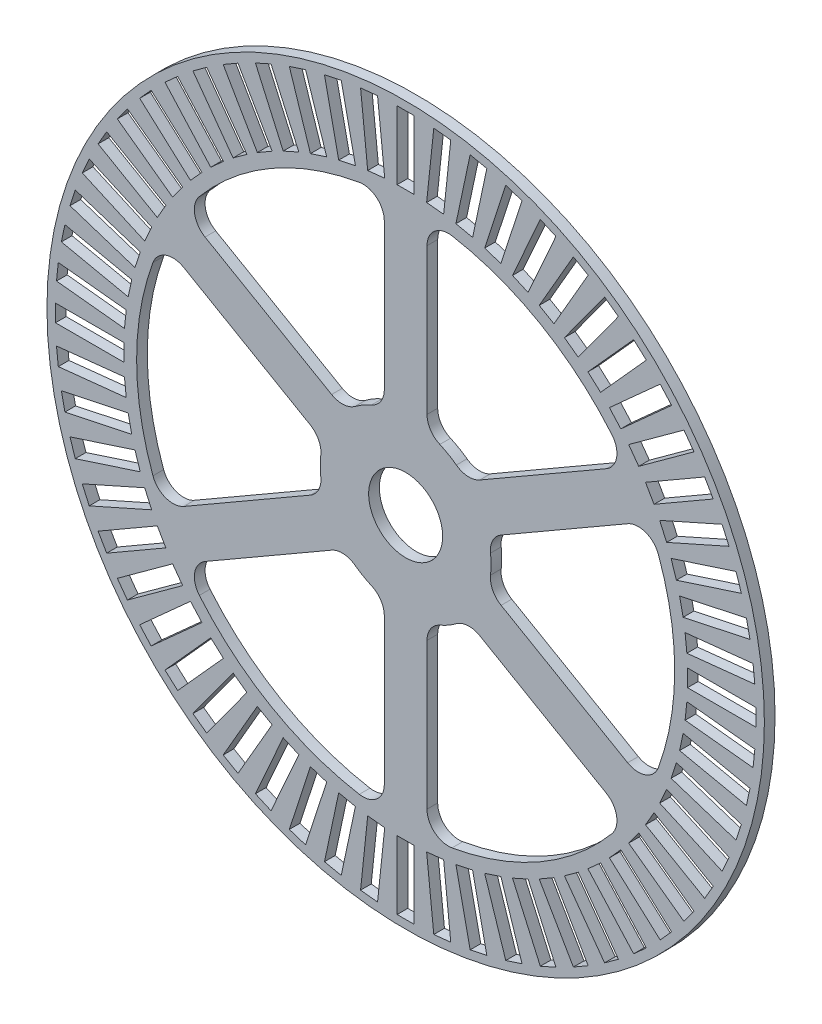
SolidWorks part; units mm, degrees
material "1023 Carbon Steel Sheet (SS)"
ref_plane "Front Plane" through (0, 0, 0) normal (0, 0, 1) x (1, 0, 0)
ref_plane "Top Plane" through (0, 0, 0) normal (0, 1, 0) x (1, 0, 0)
ref_plane "Right Plane" through (0, 0, 0) normal (1, 0, 0) x (0, 0, -1)
sketch "Sketch1" plane through (0, 0, 0) normal (0, 0, 1) x (1, 0, 0)
  circle A0 centre (0, 0) radius 40.005
  circle A1 centre (0, 0) radius 53.34
  dimension "D1" = 106.68
  dimension "D2" = 13.335
extrude "Boss-Extrude1" add sketch "Sketch1" along normal blind 1.5875
sketch "Sketch4" plane through (0, 0, 1.5875) normal (0, 0, 1) x (1, 0, 0)
  line L1 (-1.27, 52.07) -> (1.27, 52.07)
  line L2 (-1.27, 52.07) -> (-1.27, 41.91)
  line L3 (-1.27, 41.91) -> (1.27, 41.91)
  line L4 (1.27, 52.07) -> (1.27, 41.91)
  line L5 (-1.27, 52.07) -> (1.27, 41.91) construction
  line L6 (-1.27, 41.91) -> (1.27, 52.07) construction
  point P0 (0, 46.99)
  dimension "D1" = 2.54
  dimension "D2" = 10.16
  dimension "D3" = 46.99
extrude "Cut-Extrude3" cut sketch "Sketch4" against normal blind 5.08 contours L1 L4 L3 L2
pattern_circular "CirPattern2" count 60 over 360 about axis through (0, 0, 0) along (0, 0, 1) of "Cut-Extrude3"
sketch "Sketch7" plane through (0, 0, 0) normal (0, 0, -1) x (-1, 0, 0)
  line L0 (-1.905, 0) -> (49998.095, 0) construction
  circle A2 centre (60.325, 0) radius 6.985
  point P6 (60.325, 0)
  dimension "D1" = 60.325
  dimension "D2" = 13.97
extrude "Cut-Extrude5" [suppressed] cut sketch "Sketch7" against normal blind 2.54
pattern_circular "CirPattern4" [suppressed] count 6 over 360
sketch "Sketch8" plane through (0, 0, 0) normal (0, 0, 1) x (1, 0, 0)
  line L0 (-3.175, 12.2967) -> (-3.175, 39.8788)
  line L1 (3.175, 12.2967) -> (3.175, 39.8788)
  line L2 (9.0618, 8.898) -> (32.9486, 22.689)
  line L3 (12.2368, 3.3987) -> (36.1236, 17.1898)
  line L4 (12.2368, -3.3987) -> (36.1236, -17.1898)
  line L5 (9.0618, -8.898) -> (32.9486, -22.689)
  line L6 (3.175, -12.2967) -> (3.175, -39.8788)
  line L7 (-3.175, -12.2967) -> (-3.175, -39.8788)
  line L8 (-9.0618, -8.898) -> (-32.9486, -22.689)
  line L9 (-12.2368, -3.3987) -> (-36.1236, -17.1898)
  line L10 (-12.2368, 3.3987) -> (-36.1236, 17.1898)
  line L11 (-9.0618, 8.898) -> (-32.9486, 22.689)
  circle A1 centre (0, 0) radius 40.005 construction
  arc A2 (-32.9486, 22.689) -> (-36.1236, 17.1898) centre (0, 0) ccw
  arc A3 (-36.1236, -17.1898) -> (-32.9486, -22.689) centre (0, 0) ccw
  arc A4 (-3.175, -39.8788) -> (3.175, -39.8788) centre (0, 0) ccw
  arc A5 (32.9486, -22.689) -> (36.1236, -17.1898) centre (0, 0) ccw
  arc A6 (36.1236, 17.1898) -> (32.9486, 22.689) centre (0, 0) ccw
  arc A7 (3.175, 39.8788) -> (-3.175, 39.8788) centre (0, 0) ccw
  circle A8 centre (0, 0) radius 5.5
  arc A9 (-12.2368, 3.3987) -> (-12.2368, -3.3987) centre (0, 0) ccw
  arc A10 (-3.175, 12.2967) -> (-9.0618, 8.898) centre (0, 0) ccw
  arc A11 (9.0618, 8.898) -> (3.175, 12.2967) centre (0, 0) ccw
  arc A12 (12.2368, -3.3987) -> (12.2368, 3.3987) centre (0, 0) ccw
  arc A13 (3.175, -12.2967) -> (9.0618, -8.898) centre (0, 0) ccw
  arc A14 (-9.0618, -8.898) -> (-3.175, -12.2967) centre (0, 0) ccw
  point P32 (0, 0)
  dimension "D1" = 11
  dimension "D4" = 25.4
  dimension "D2" = 6.35
  dimension "D3" = 6
extrude "Boss-Extrude2" add sketch "Sketch8" along normal blind 1.5875
fillet "Fillet1" radius 3.175 24 edges at (12.2368, -3.3987, 0.7937) (12.2368, 3.3987, 0.7937) (9.0618, -8.898, 0.7937) (3.175, -12.2967, 0.7937) (-3.175, -12.2967, 0.7937) (-9.0618, -8.898, 0.7937) (-12.2368, 3.3987, 0.7937) (-12.2368, -3.3987, 0.7937) (-3.175, 12.2967, 0.7937) (-9.0618, 8.898, 0.7937) (3.175, 12.2967, 0.7937) (9.0618, 8.898, 0.7937) (3.175, 39.8788, 0.7937) (32.9486, 22.689, 0.7937) (36.1236, 17.1898, 0.7937) (36.1236, -17.1898, 0.7937) (32.9486, -22.689, 0.7937) (3.175, -39.8788, 0.7937) (-3.175, -39.8788, 0.7937) (-32.9486, -22.689, 0.7937) (-36.1236, -17.1898, 0.7937) (-36.1236, 17.1898, 0.7937) (-32.9486, 22.689, 0.7937) (-3.175, 39.8788, 0.7937)
